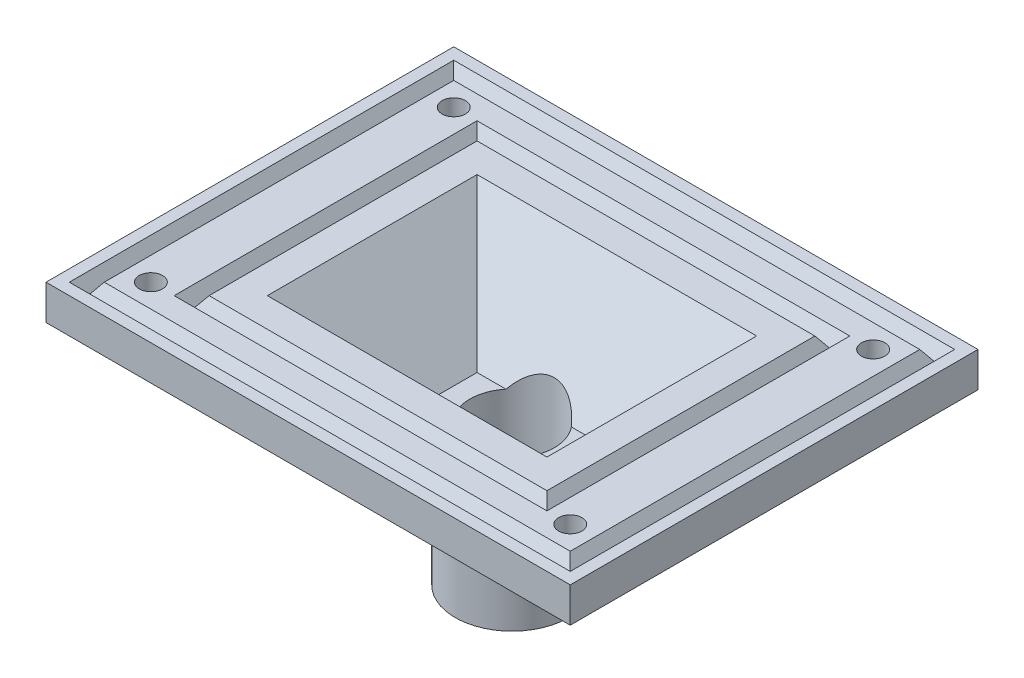
SolidWorks part; units mm, degrees
ref_plane "Front Plane" through (0, 0, 0) normal (0, 0, 1) x (1, 0, 0)
ref_plane "Top Plane" through (0, 0, 0) normal (0, 1, 0) x (1, 0, 0)
ref_plane "Right Plane" through (0, 0, 0) normal (1, 0, 0) x (0, 0, -1)
sketch "Sketch1" plane through (0, 0, 0) normal (0, 1, 0) x (1, 0, 0)
  line L1 (45, -35) -> (-45, -35)
  line L2 (45, -35) -> (45, 35)
  line L3 (45, 35) -> (-45, 35)
  line L4 (-45, -35) -> (-45, 35)
  line L5 (45, -35) -> (-45, 35) construction
  line L6 (45, 35) -> (-45, -35) construction
  point P0 (0, 0)
  dimension "D1" = 90
  dimension "D2" = 70
extrude "Base Plate" add sketch "Sketch1" along normal blind 6
sketch "Sketch4" plane through (0, 6, 0) normal (0, 1, 0) x (1, 0, 0)
  line L0 (-43, -33) -> (-43, 33)
  line L1 (-43, 33) -> (43, 33)
  line L2 (43, 33) -> (43, -33)
  line L3 (43, -33) -> (-43, -33)
  line L4 (-40, -30) -> (-40, 30)
  line L5 (-40, 30) -> (40, 30)
  line L6 (40, 30) -> (40, -30)
  line L7 (40, -30) -> (-40, -30)
  line L8 (45, -35) -> (45, 35) construction
  line L9 (-45, 35) -> (-45, -35) construction
  line L10 (-45, -35) -> (45, -35) construction
  line L11 (45, 35) -> (-45, 35) construction
  dimension "D1" = 2
  dimension "D2" = 3
  dimension "D3" = 2
  dimension "D4" = 3
  dimension "D5" = 2
  dimension "D6" = 3
  dimension "D7" = 3
  dimension "D8" = 2
extrude "Sealant Cut - Outer" cut sketch "Sketch4" against normal blind 5 draft 35
sketch "Sketch7" plane through (0, 6, 0) normal (0, 1, 0) x (1, 0, 0)
  line L0 (40, 30) -> (-40, 30) construction
  line L1 (-40, 30) -> (-40, -30) construction
  line L2 (0, 0) -> (-11.5051, 0) construction
  line L4 (0, 13.9859) -> (0, 0) construction
  circle A0 centre (-36, 26) radius 2
  circle A1 centre (-36, -26) radius 2
  circle A2 centre (36, -26) radius 2
  circle A3 centre (36, 26) radius 2
  dimension "D1" = 4
  dimension "D2" = 4
  dimension "D3" = 4
extrude "Scre Cut" cut sketch "Sketch7" against normal blind 5
sketch "Sketch8" plane through (0, 0, 0) normal (0, -1, 0) x (1, 0, 0)
  line L0 (0, 0) -> (0, -6.6439) construction
  line L2 (-4.9872, 0) -> (0, 0) construction
  circle A0 centre (-36, -26) radius 2.75
  circle A1 centre (-36, 26) radius 2.75
  circle A2 centre (36, 26) radius 2.75
  circle A3 centre (36, -26) radius 2.75
  dimension "D1" = 5.5
sketch "Sketch12" plane through (0, 6, 0) normal (0, 1, 0) x (1, 0, 0)
  line L0 (32, -26) -> (-32, -26)
  line L1 (-32, -26) -> (-32, 26)
  line L2 (-32, 26) -> (32, 26)
  line L3 (32, 26) -> (32, -26)
  line L4 (29, -23) -> (-29, -23)
  line L5 (-29, -23) -> (-29, 23)
  line L6 (-29, 23) -> (29, 23)
  line L7 (29, 23) -> (29, -23)
  line L8 (40, 30) -> (-40, 30) construction
  circle A0 centre (36, -26) radius 2 construction
  circle A3 centre (-36, 26) radius 2 construction
  circle A4 centre (36, 26) radius 2 construction
  dimension "D1" = 4
  dimension "D2" = 3
  dimension "D3" = 4
  dimension "D4" = 4
  dimension "D5" = 4
  dimension "D6" = 3
  dimension "D7" = 3
  dimension "D8" = 3
extrude "Sealant Cut - Inner" cut sketch "Sketch12" against normal blind 3 draft 35
sketch "Sketch13" plane through (0, 6, 0) normal (0, 1, 0) x (1, 0, 0)
  line L0 (29, -23) -> (29, 23) construction
  line L1 (-24, 18) -> (24, 18)
  line L2 (-24, 18) -> (-24, -18)
  line L3 (-24, -18) -> (24, -18)
  line L4 (24, 18) -> (24, -18)
  line L5 (-24, 18) -> (24, -18) construction
  line L6 (-24, -18) -> (24, 18) construction
  line L7 (-29, -23) -> (29, -23) construction
  point P0 (0, 0)
  dimension "D1" = 5
  dimension "D2" = 5
sketch "Sketch14" plane through (0, 0, 0) normal (0, -1, 0) x (1, 0, 0)
  line L1 (32.5, -22.5) -> (-32.5, -22.5)
  line L2 (32.5, -22.5) -> (32.5, 22.5)
  line L3 (32.5, 22.5) -> (-32.5, 22.5)
  line L4 (-32.5, -22.5) -> (-32.5, 22.5)
  line L5 (32.5, -22.5) -> (-32.5, 22.5) construction
  line L6 (32.5, 22.5) -> (-32.5, -22.5) construction
  point P0 (0, 0)
  dimension "D1" = 65
  dimension "D2" = 45
extrude "Base Block" add sketch "Sketch14" along normal blind 14
extrude "Drain" cut sketch "Sketch13" against normal blind 16 draft 40
sketch "Sketch15" plane through (0, -14, 0) normal (0, -1, 0) x (1, 0, 0)
  circle A0 centre (0, 0) radius 9.75
  dimension "D1" = 19.5
extrude "Hose connector" add sketch "Sketch15" along normal blind 20
sketch "Sketch16" plane through (0, -34, 0) normal (0, -1, 0) x (1, 0, 0)
  circle A0 centre (0, 0) radius 7.25
  circle A1 centre (0, 0) radius 9.75 construction
  dimension "D1" = 2.5
extrude "Drain Hole" cut sketch "Sketch16" against normal through all contours A0
fillet "Fillet1" radius 10 1 edges at (-32.5, -7, -22.5)
fillet "Fillet2" radius 10 1 edges at (32.5, -7, -22.5)
fillet "Fillet3" radius 10 1 edges at (32.5, -7, 22.5)
fillet "Fillet4" radius 10 1 edges at (-32.5, -7, 22.5)
extrude "Srew Heads" cut sketch "Sketch8" against normal blind 20 draft 45
fillet "Fillet5" radius 10 8 edges at (0, -14, -22.5) (-29.5711, -14, -19.5711) (32.5, -14, 0) (29.5711, -14, -19.5711) (0, -14, 22.5) (29.5711, -14, 19.5711) (-32.5, -14, 0) (-29.5711, -14, 19.5711)
